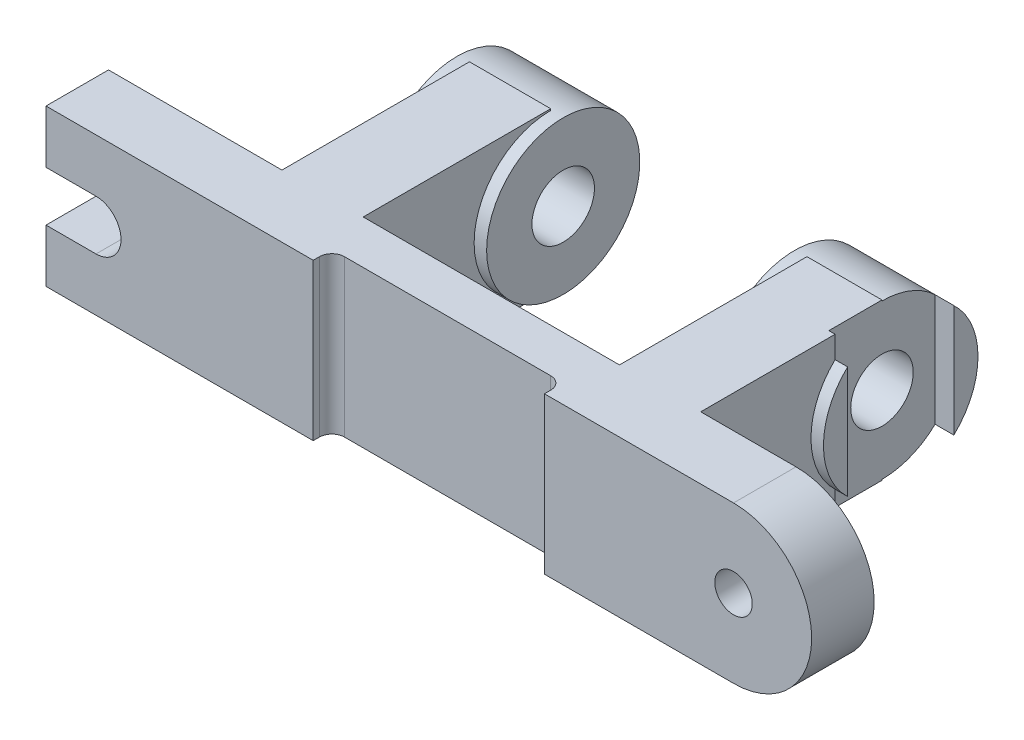
SolidWorks part; units mm, degrees
ref_plane "Front Plane" through (0, 0, 0) normal (0, 0, 1) x (1, 0, 0)
ref_plane "Top Plane" through (0, 0, 0) normal (0, 1, 0) x (1, 0, 0)
ref_plane "Right Plane" through (0, 0, 0) normal (1, 0, 0) x (0, 0, -1)
sketch "Sketch1" plane through (0, 0, 0) normal (0, 0, 1) x (1, 0, 0)
  line L0 (-165.913, -4.3043) -> (54.087, -4.3043)
  line L1 (54.087, 45.6957) -> (-165.913, 45.6957)
  line L2 (-165.913, 45.6957) -> (-165.913, 28.6957)
  line L3 (-165.913, 28.6957) -> (-149.913, 28.6957)
  line L4 (-149.913, 12.6957) -> (-165.913, 12.6957)
  line L5 (-165.913, 12.6957) -> (-165.913, -4.3043)
  arc A3 (54.087, 45.6957) -> (54.087, -4.3043) centre (54.087, 20.6957) cw
  arc A4 (-149.913, 12.6957) -> (-149.913, 28.6957) centre (-149.913, 20.6957) ccw
  dimension "D1" = 16
  dimension "D2" = 50
  dimension "D3" = 25
  dimension "D4" = 220
  dimension "D5" = 220
  dimension "D6" = 220
  dimension "D7" = 16
extrude "Boss-Extrude1" add sketch "Sketch1" along normal blind 20
sketch "Sketch2" plane through (0, 45.6957, 0) normal (0, 1, 0) x (1, 0, 0)
  line L0 (-43.413, 79.4375) -> (-43.413, -76.2645) construction
  line L1 (-165.913, -20) -> (-165.913, 0) construction
  line L2 (54.087, -20) -> (-165.913, -20) construction
  line L3 (-80.413, -20) -> (-6.413, -20)
  line L4 (-80.413, -20) -> (-80.413, -18)
  line L5 (-76.413, -14) -> (-10.413, -14)
  line L6 (-6.413, -20) -> (-6.413, -18)
  line L7 (54.087, 0) -> (-165.913, 0) construction
  arc A0 (-6.413, -18) -> (-10.413, -14) centre (-10.413, -18) ccw
  arc A1 (-80.413, -18) -> (-76.413, -14) centre (-76.413, -18) cw
  dimension "D5" = 4
  dimension "D1" = 122.5
  dimension "D2" = 37
  dimension "D3" = 74
  dimension "D4" = 14
extrude "Cut-Extrude1" cut sketch "Sketch2" against normal blind 80 contours L5 A0 L6 L3 L4 A1
hole_wizard "M14x2.0 Tapped Hole2" positions "Sketch9" profile "Sketch10" tap size "M14x2.0" standard "ANSI Metric" end condition through all
sketch "Sketch9" plane through (0, 0, 0) normal (0, 0, -1) x (-1, 0, 0)
  point P0 (-54.087, 20.6957)
sketch "Sketch10" plane through (54.087, 20.6957, 0) normal (1, 0, 0) x (0, 1, 0)
  line L0 (0, 0) -> (0, 20)
  line L1 (0, 20) -> (6, 20)
  line L2 (6, 20) -> (6, 1.025)
  line L3 (6, 1.025) -> (7.025, 0)
  line L5 (7.025, 0) -> (0, 0)
  line L6 (-6, 1.025) -> (-7.025, 0) construction
  line L11 (0, -6.35) -> (0, 107.95) construction
  dimension "Thru Tap Drill Dia." = 12
  dimension "Thru Tap Drill Depth" = 20
  dimension "Near C'Sink Dia." = 14.05
  dimension "Near C'Sink Angle" = 90
cosmetic thread "Hole Thread3" parameters "D2"=14
sketch "Sketch11" plane through (0, 0, 0) normal (0, 0, -1) x (-1, 0, 0)
  line L0 (165.913, -4.3043) -> (-54.087, -4.3043) construction
  line L1 (110.413, -4.3043) -> (84.413, -4.3043)
  line L2 (110.413, -4.3043) -> (110.413, 45.6957)
  line L3 (110.413, 45.6957) -> (84.413, 45.6957)
  line L4 (84.413, -4.3043) -> (84.413, 45.6957)
  line L5 (-54.087, 45.6957) -> (165.913, 45.6957) construction
  line L6 (43.413, -40.8822) -> (43.413, 65.089) construction
  line L7 (2.413, -4.3043) -> (-23.587, -4.3043)
  line L8 (2.413, -4.3043) -> (2.413, 45.6957)
  line L9 (2.413, 45.6957) -> (-23.587, 45.6957)
  line L10 (-23.587, -4.3043) -> (-23.587, 45.6957)
  line L11 (165.913, 45.6957) -> (165.913, 28.6957) construction
  dimension "D1" = 26
  dimension "D2" = 26
  dimension "D3" = 82
  dimension "D4" = 122.5
  dimension "D5" = 41
extrude "Boss-Extrude2" add sketch "Sketch11" along normal blind 60
sketch "Sketch12" plane through (-110.413, 0, 0) normal (-1, 0, 0) x (0, 0, 1)
  line L0 (-60, -4.3043) -> (-60, 45.6957) construction
  circle A0 centre (-60, 20.6957) radius 24.5097
extrude "Boss-Extrude3" add sketch "Sketch12" against normal blind 34 from offset 4
sketch "Sketch13" plane through (-2.413, 0, 0) normal (-1, 0, 0) x (0, 0, 1)
  line L0 (-60, -4.3043) -> (-60, 45.6957) construction
  circle A0 centre (-60, 20.6957) radius 24.7256
extrude "Boss-Extrude4" add sketch "Sketch13" against normal blind 34 from offset 4
sketch "Sketch14" plane through (27.587, 0, 0) normal (1, 0, 0) x (0, 0, -1)
  circle A0 centre (60, 20.6957) radius 10
  dimension "D1" = 20
extrude "Cut-Extrude2" cut sketch "Sketch14" against normal blind 234
sketch "Sketch15" plane through (27.587, 0, 0) normal (1, 0, 0) x (0, 0, -1)
  line L1 (77, 70.8111) -> (43, 70.8111)
  line L2 (77, 70.8111) -> (77, -29.4198)
  line L3 (77, -29.4198) -> (43, -29.4198)
  line L4 (43, 70.8111) -> (43, -29.4198)
  line L5 (77, 70.8111) -> (43, -29.4198) construction
  line L6 (77, -29.4198) -> (43, 70.8111) construction
  point P0 (60, 20.6957)
  dimension "D1" = 34
extrude "Cut-Extrude3" cut sketch "Sketch15" against normal blind 6
ref_plane "Plane1" through (0, 20.6957, 0) normal (0, 1, 0) x (1, 0, 0)
sketch "Sketch16" plane through (0, 20.6957, 0) normal (0, 1, 0) x (1, 0, 0)
  line L0 (-114.3821, 37.1751) -> (-130.8035, 0)
  line L1 (-110.413, 0) -> (-165.913, 0) construction
  point P5 (0, 0)
  point P6 (-114.413, 35.4903)
  point P7 (0, 0)
  point P8 (-114.413, 35.4903)
  point P9 (0, 0)
  point P10 (-114.3821, 37.1751)
rib "Rib6" sketch "Sketch16" sketch "Sketch16" thickness 16 extrusion direction parallel to sketch draft on no parameters "D1"=16
